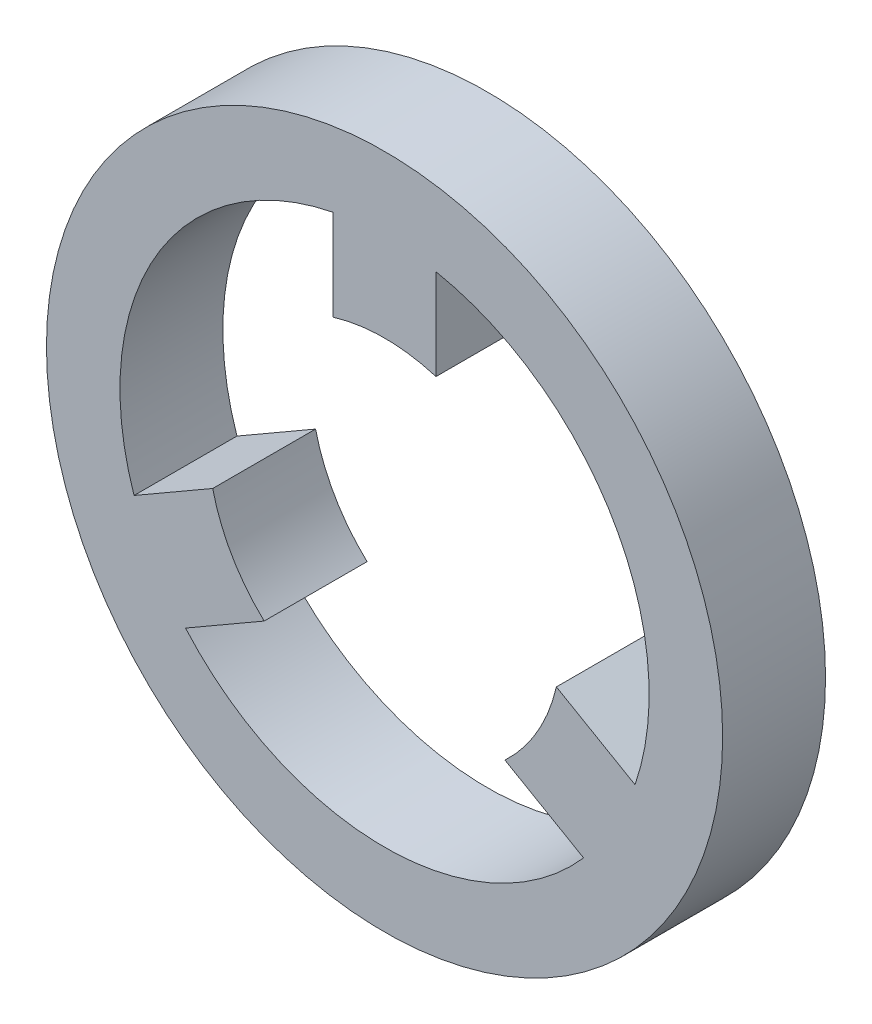
SolidWorks part; units mm, degrees
ref_plane "Front Plane" through (0, 0, 0) normal (0, 0, 1) x (1, 0, 0)
ref_plane "Top Plane" through (0, 0, 0) normal (0, 1, 0) x (1, 0, 0)
ref_plane "Right Plane" through (0, 0, 0) normal (1, 0, 0) x (0, 0, -1)
sketch "Sketch1" plane through (0, 0, 0) normal (0, 0, 1) x (1, 0, 0)
  line L0 (8.5205, -2.8986) -> (0.875, 1.5155)
  line L2 (-1.75, 8.8282) -> (-1.75, 0)
  line L3 (-1.75, 0) -> (1.75, 0)
  line L4 (1.75, 8.8282) -> (1.75, 0)
  line L5 (0.875, 1.5155) -> (-0.875, -1.5155)
  line L6 (6.7705, -5.9297) -> (-0.875, -1.5155)
  line L7 (-6.7705, -5.9297) -> (0.875, -1.5155)
  line L8 (0.875, -1.5155) -> (-0.875, 1.5155)
  line L9 (-8.5205, -2.8986) -> (-0.875, 1.5155)
  circle A0 centre (0, 0) radius 9
  circle A1 centre (0, 0) radius 6
  circle A2 centre (0, 0) radius 11.5
  point P19 (0, 0)
  dimension "D1" = 18
  dimension "D2" = 12
  dimension "D5" = 23
  dimension "D3" = 3.5
  dimension "D4" = 3
extrude "Boss-Extrude1" add sketch "Sketch1" along normal blind 3.5 contours A2 A0 | A1 L4 A0 L2 | A1 L9 A0 L7 | A1 L6 A0 L0
